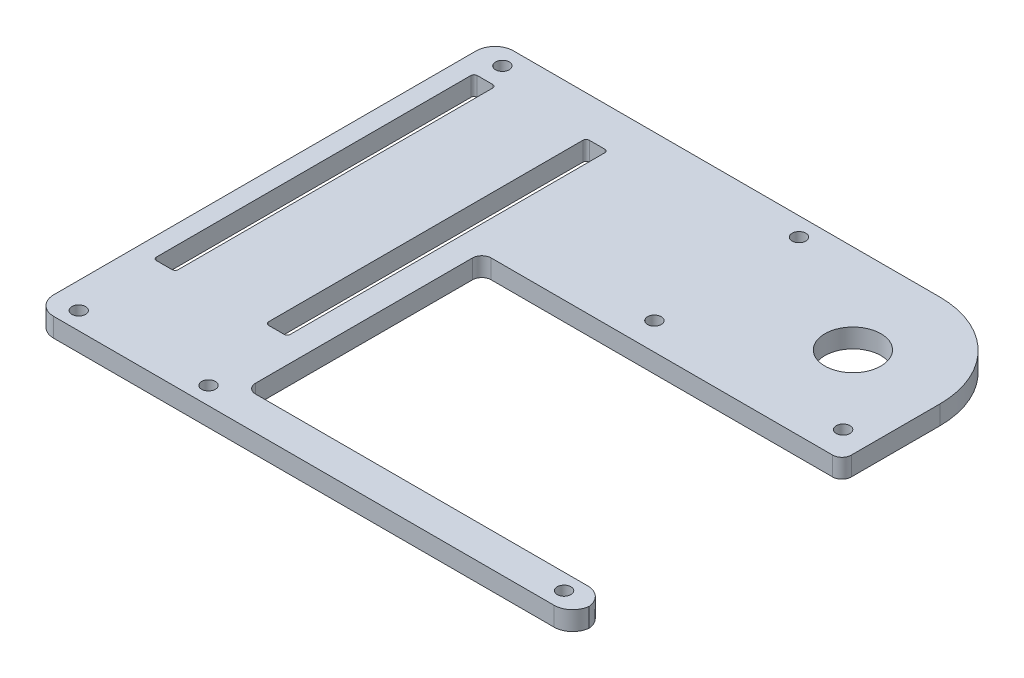
SolidWorks part; units mm, degrees
material "PMMA"
ref_plane "Front Plane" through (0, 0, 0) normal (0, 0, 1) x (1, 0, 0)
ref_plane "Top Plane" through (0, 0, 0) normal (0, 1, 0) x (1, 0, 0)
ref_plane "Right Plane" through (0, 0, 0) normal (1, 0, 0) x (0, 0, -1)
sketch "Sketch2" plane through (0, 0, 0) normal (0, 1, 0) x (1, 0, 0)
  line L0 (28.5, -66.94) -> (28.5, -32.09)
  line L1 (3, 0) -> (71.45, 0)
  line L2 (0, -3) -> (0, -70.84)
  line L3 (3, -73.84) -> (83.3401, -73.84)
  line L4 (86.33, -14.88) -> (86.33, -29.09)
  line L5 (30, -30.59) -> (84.83, -30.59)
  line L6 (30, -68.44) -> (83.33, -68.44)
  line L8 (6.5, -6.84) -> (6.5, -57.34)
  line L9 (3, -6.34) -> (24.5, -6.34) construction
  line L10 (3, -6.84) -> (3, -57.34)
  line L11 (3, -57.84) -> (24.5, -57.84) construction
  line L12 (24.5, -6.84) -> (24.5, -57.34)
  line L17 (21, -6.84) -> (21, -57.34)
  line L18 (3.5, -6.34) -> (6, -6.34)
  line L19 (21.5, -6.34) -> (24, -6.34)
  line L20 (3.5, -57.84) -> (6, -57.84)
  line L21 (21.5, -57.84) -> (24, -57.84)
  arc A0 (86.33, -14.88) -> (71.45, 0) centre (71.45, -14.88) ccw
  circle A1 centre (4.19, -71.01) radius 1.1
  circle A2 centre (25.03, -71.01) radius 1.1
  circle A3 centre (4.19, -2.98) radius 1.1
  circle A4 centre (51.82, -2.98) radius 1.1
  circle A5 centre (51.82, -26.2) radius 1.1
  circle A6 centre (82.13, -71.01) radius 1.1
  circle A7 centre (82.13, -26.2) radius 1.1
  circle A8 centre (71.83, -14.33) radius 4.5
  arc A9 (86.3196, -71.19) -> (83.3401, -73.84) centre (83.3401, -70.84) cw
  arc A10 (0, -70.84) -> (3, -73.84) centre (3, -70.84) ccw
  arc A11 (3, 0) -> (0, -3) centre (3, -3) ccw
  arc A12 (86.3196, -71.19) -> (83.33, -68.44) centre (83.33, -71.44) ccw
  arc A13 (28.5, -66.94) -> (30, -68.44) centre (30, -66.94) ccw
  arc A14 (28.5, -32.09) -> (30, -30.59) centre (30, -32.09) cw
  arc A15 (86.33, -29.09) -> (84.83, -30.59) centre (84.83, -29.09) cw
  arc A16 (6.5, -57.34) -> (6, -57.84) centre (6, -57.34) cw
  arc A17 (3, -57.34) -> (3.5, -57.84) centre (3.5, -57.34) ccw
  arc A18 (21, -57.34) -> (21.5, -57.84) centre (21.5, -57.34) ccw
  arc A19 (24.5, -57.34) -> (24, -57.84) centre (24, -57.34) cw
  arc A20 (24.5, -6.84) -> (24, -6.34) centre (24, -6.84) ccw
  arc A21 (21, -6.84) -> (21.5, -6.34) centre (21.5, -6.84) cw
  arc A22 (6, -6.34) -> (6.5, -6.84) centre (6, -6.84) cw
  arc A23 (3, -6.84) -> (3.5, -6.34) centre (3.5, -6.84) cw
  point P37 (86.33, -73.84)
  point P40 (0, -73.84)
  point P43 (0, 0)
  point P46 (86.33, -68.34)
  point P55 (6.5, -57.84)
  point P61 (21, -57.84)
  point P70 (21, -6.34)
  point P73 (6.5, -6.34)
  dimension "D1" = 14.88
  dimension "D6" = 2.2
  dimension "D28" = 9
  dimension "D29" = 3
  dimension "D30" = 3
  dimension "D31" = 3
  dimension "D32" = 3
  dimension "D33" = 1.5
  dimension "D34" = 1.5
  dimension "D35" = 1.5
  dimension "D36" = 0.5
  dimension "D37" = 0.5
  dimension "D38" = 0.5
  dimension "D39" = 0.5
  dimension "D40" = 0.5
  dimension "D41" = 0.5
  dimension "D42" = 0.5
  dimension "D43" = 0.5
  dimension "D2" = 73.84
  dimension "D3" = 86.33
  dimension "D4" = 2.83
  dimension "D5" = 4.19
  dimension "D7" = 25.03
  dimension "D8" = 2.83
  dimension "D9" = 2.98
  dimension "D10" = 2.98
  dimension "D11" = 47.63
  dimension "D12" = 23.22
  dimension "D13" = 4.2
  dimension "D14" = 4.2
  dimension "D15" = 2.83
  dimension "D16" = 51.82
  dimension "D17" = 26.2
  dimension "D18" = 28.5
  dimension "D19" = 43.25
  dimension "D20" = 5.4
  dimension "D21" = 16
  dimension "D22" = 21.5
  dimension "D23" = 3
  dimension "D24" = 51.5
  dimension "D25" = 3.5
  dimension "D26" = 3.5
  dimension "D27" = 14.33
  dimension "D44" = 14.5
extrude "Boss-Extrude1" add sketch "Sketch2" along normal blind 3.048
